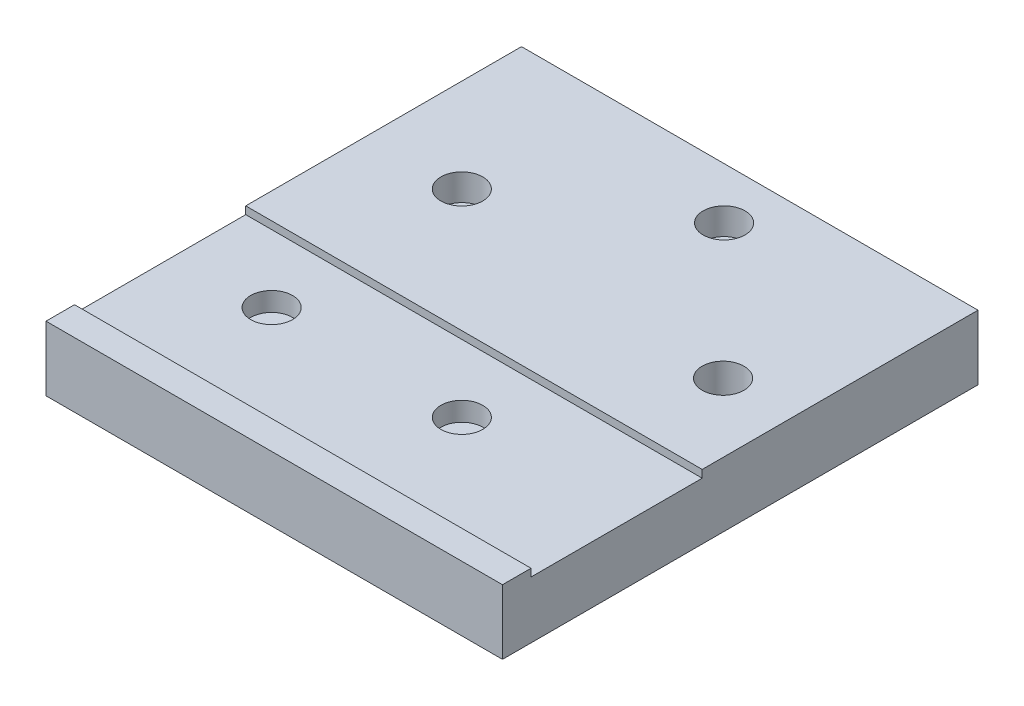
SolidWorks part; units mm, degrees
ref_plane "Front Plane" through (0, 0, 0) normal (0, 0, 1) x (1, 0, 0)
ref_plane "Top Plane" through (0, 0, 0) normal (0, 1, 0) x (1, 0, 0)
ref_plane "Right Plane" through (0, 0, 0) normal (1, 0, 0) x (0, 0, -1)
sketch "Sketch1" plane through (0, 0, 0) normal (0, 1, 0) x (1, 0, 0)
  line L1 (-60, -27.5) -> (60, -27.5)
  line L2 (-60, -27.5) -> (-60, 27.5)
  line L3 (-60, 27.5) -> (60, 27.5)
  line L4 (60, -27.5) -> (60, 27.5)
  line L5 (-60, -27.5) -> (60, 27.5) construction
  line L6 (-60, 27.5) -> (60, -27.5) construction
  point P0 (0, 0)
  dimension "D1" = 55
  dimension "D2" = 120
extrude "Boss-Extrude1" add sketch "Sketch1" along normal blind 5
sketch "Sketch2" plane through (0, 5, 0) normal (0, 1, 0) x (1, 0, 0)
  line L0 (60, -27.5) -> (60, 27.5) construction
  line L1 (-60, -27.5) -> (60, -27.5)
  line L2 (-60, -27.5) -> (-60, -20)
  line L3 (-60, -20) -> (60, -20)
  line L4 (60, -27.5) -> (60, -20)
  dimension "D1" = 7.5
extrude "Boss-Extrude2" add sketch "Sketch2" along normal blind 20
sketch "Sketch3" plane through (0, 5, 0) normal (0, 1, 0) x (1, 0, 0)
  line L0 (-60, 27.5) -> (-60, -20) construction
  line L1 (60, 27.5) -> (-60, 27.5)
  line L2 (60, 27.5) -> (60, 25)
  line L3 (60, 25) -> (-60, 25)
  line L4 (-60, 27.5) -> (-60, 25)
  dimension "D1" = 2.5
extrude "Boss-Extrude4" add sketch "Sketch3" along normal blind 20
sketch "Sketch8" plane through (-60, 0, 0) normal (-1, 0, 0) x (0, 0, 1)
  line L0 (-27.5, 0) -> (-27.5, 25)
  line L1 (-27.5, 25) -> (-25, 25)
  line L2 (-25, 25) -> (-25, 5)
  line L3 (-25, 5) -> (20, 5)
  line L4 (20, 5) -> (20, 25)
  line L5 (20, 25) -> (27.5, 25)
  line L6 (27.5, 25) -> (27.5, 0)
  line L7 (27.5, 0) -> (-27.5, 0)
extrude "Boss-Extrude5" add sketch "Sketch8" along normal blind 190
sketch "Sketch9" plane through (0, 0, -27.5) normal (0, 0, -1) x (-1, 0, 0)
  line L0 (-60, 0) -> (-60, 25)
  line L1 (-60, 25) -> (250, 25)
  line L2 (250, 25) -> (250, 0)
  line L3 (250, 0) -> (-60, 0)
extrude "Boss-Extrude6" add sketch "Sketch9" along normal blind 70
sketch "Sketch14" plane through (0, 0, 0) normal (0, -1, 0) x (-1, 0, 0)
  circle A0 centre (225.4453, 7.2552) radius 5.5
  circle A1 centre (175.4453, 7.2552) radius 5.5
  circle A2 centre (225.4453, 57.2552) radius 5.5
  circle A3 centre (148.0182, 48.5) radius 5.5
  circle A4 centre (183.2409, 83.9875) radius 5.5
  dimension "D1" = 11
  dimension "D3" = 11
  dimension "D5" = 11
  dimension "D6" = 11
  dimension "D8" = 11
  dimension "D2" = 50
  dimension "D4" = 50
  dimension "D7" = 50
extrude "Cut-Extrude5" cut sketch "Sketch14" against normal blind 153
sketch "Sketch15" plane through (60, 0, 0) normal (1, 0, 0) x (0, 0, -1)
  line L1 (-27.5, 25) -> (97.5, 25)
  line L2 (-27.5, 25) -> (-27.5, 0)
  line L3 (-27.5, 0) -> (97.5, 0)
  line L4 (97.5, 25) -> (97.5, 0)
extrude "Cut-Extrude6" cut sketch "Sketch15" against normal blind 190
sketch "Sketch16" plane through (0, 0, 0) normal (0, -1, 0) x (-1, 0, 0)
  line L1 (130, -27.5) -> (250, -27.5)
  line L2 (130, -27.5) -> (130, 97.5)
  line L3 (130, 97.5) -> (250, 97.5)
  line L4 (250, -27.5) -> (250, 97.5)
extrude "Boss-Extrude8" add sketch "Sketch16" along normal blind 10
sketch "Sketch17" plane through (0, 25, 0) normal (0, 1, 0) x (1, 0, 0)
  line L1 (-250, 97.5) -> (-130, 97.5)
  line L2 (-250, 97.5) -> (-250, -27.5)
  line L3 (-250, -27.5) -> (-130, -27.5)
  line L4 (-130, 97.5) -> (-130, -27.5)
extrude "Cut-Extrude7" cut sketch "Sketch17" against normal blind 18
sketch "Sketch18" plane through (0, 7, 0) normal (0, 1, 0) x (1, 0, 0)
  circle A0 centre (-148.0182, 48.5) radius 5.5
extrude "Cut-Extrude8" cut sketch "Sketch18" against normal blind 18
sketch "Sketch19" plane through (0, 7, 0) normal (0, 1, 0) x (1, 0, 0)
  circle A0 centre (-148.0182, 48.5) radius 5.5
